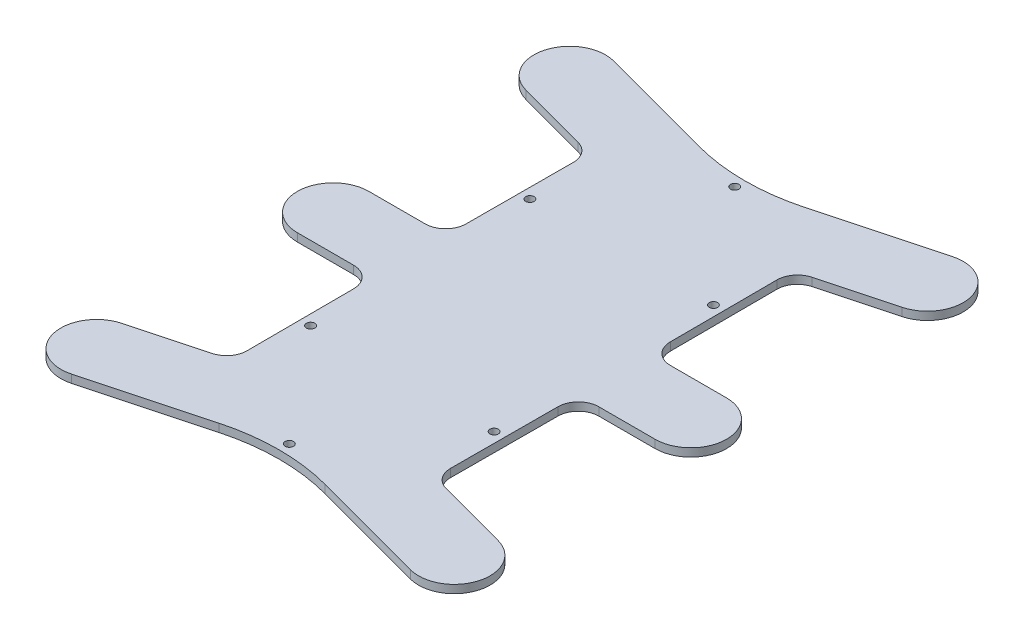
SolidWorks part; units mm, degrees
ref_plane "Front Plane" through (0, 0, 0) normal (0, 0, 1) x (1, 0, 0)
ref_plane "Top Plane" through (0, 0, 0) normal (0, 1, 0) x (1, 0, 0)
ref_plane "Right Plane" through (0, 0, 0) normal (1, 0, 0) x (0, 0, -1)
sketch "Sketch1" plane through (0, 0, 0) normal (0, 1, 0) x (1, 0, 0)
  line L0 (0, 32.1883) -> (0, -21.4181) construction
  line L1 (0, 0) -> (27.1703, 0) construction
  line L2 (-70, 14) -> (-40, 14)
  line L3 (-40, 14) -> (-39.8161, 70)
  line L4 (-39.8161, 70) -> (-73.6235, 79.0587)
  line L5 (-66.3765, 106.1046) -> (0, 88.3191)
  line L10 (-66.3765, 106.1046) -> (-73.6235, 79.0587) construction
  line L12 (-70, 14) -> (-70, -14) construction
  line L14 (-66.3765, -106.1046) -> (0, -88.3191)
  line L15 (-39.8161, -70) -> (-73.6235, -79.0587)
  line L16 (-40, -14) -> (-39.8161, -70)
  line L17 (-70, -14) -> (-40, -14)
  line L18 (66.3765, -106.1046) -> (0, -88.3191)
  line L19 (66.3765, 106.1046) -> (0, 88.3191)
  line L20 (70, 14) -> (70, -14) construction
  line L21 (66.3765, 106.1046) -> (73.6235, 79.0587) construction
  line L22 (70, -14) -> (40, -14)
  line L23 (40, -14) -> (39.8161, -70)
  line L24 (39.8161, -70) -> (73.6235, -79.0587)
  line L25 (39.8161, 70) -> (73.6235, 79.0587)
  line L26 (40, 14) -> (39.8161, 70)
  line L27 (70, 14) -> (40, 14)
  arc A0 (-70, 14) -> (-70, -14) centre (-70, 0) ccw
  arc A1 (-66.3765, 106.1046) -> (-73.6235, 79.0587) centre (-70, 92.5816) ccw
  arc A11 (-66.3765, -106.1046) -> (-73.6235, -79.0587) centre (-70, -92.5816) cw
  arc A18 (66.3765, -106.1046) -> (73.6235, -79.0587) centre (70, -92.5816) ccw
  arc A22 (66.3765, 106.1046) -> (73.6235, 79.0587) centre (70, 92.5816) cw
  arc A23 (70, 14) -> (70, -14) centre (70, 0) cw
  point P118 (-83.523, 96.2051)
  dimension "D2" = 14
  dimension "D3" = 70
  dimension "D1" = 75
  dimension "D5" = 30
  dimension "D6" = 35
  dimension "D7" = 56
extrude "Boss-Extrude1" add sketch "Sketch1" along normal blind 3.175
fillet "Fillet1" radius 80 2 edges at (0, 1.5875, -88.3191) (0, 1.5875, 88.3191)
fillet "Fillet2" radius 8 8 edges at (39.8161, 1.5875, 70) (40, 1.5875, 14) (40, 1.5875, -14) (39.8161, 1.5875, -70) (-39.8161, 1.5875, -70) (-40, 1.5875, -14) (-40, 1.5875, 14) (-39.8161, 1.5875, 70)
sketch "Sketch2" plane through (0, 3.175, 0) normal (0, 1, 0) x (1, 0, 0)
  line L0 (0, 91.1411) -> (0, -91.1411) construction
  line L1 (-84, 0) -> (84, 0) construction
  line L2 (39.9738, 21.9737) -> (39.8363, 63.8405) construction
  line L3 (-39.8363, 63.8405) -> (-39.9738, 21.9737) construction
  line L4 (-39.9051, 42.9071) -> (39.9051, 42.9071) construction
  arc A0 (-20.7055, 93.8671) -> (20.7055, 93.8671) centre (0, 171.1411) ccw construction
  arc A1 (20.7055, -93.8671) -> (-20.7055, -93.8671) centre (0, -171.1411) ccw construction
  arc A2 (-70, 14) -> (-70, -14) centre (-70, 0) ccw construction
  arc A3 (70, -14) -> (70, 14) centre (70, 0) ccw construction
  circle A4 centre (0, 87.1411) radius 1.65
  circle A5 centre (-35.905, 42.9071) radius 1.65
  circle A6 centre (35.905, 42.9071) radius 1.65
  circle A7 centre (35.905, -42.9071) radius 1.65
  circle A8 centre (0, -87.1411) radius 1.65
  circle A9 centre (-35.905, -42.9071) radius 1.65
  point P18 (39.9051, 42.9071)
  point P20 (0, 0)
  point P21 (-39.9051, 42.9071)
  dimension "D4" = 3.3
  dimension "D1" = 4
  dimension "D2" = 4
  dimension "D3" = 4
extrude "Cut-Extrude1" cut sketch "Sketch2" against normal blind 10
equation "\"D2@Sketch2\"=\"D1@Sketch2\""
equation "\"D3@Sketch2\"=\"D1@Sketch2\""
